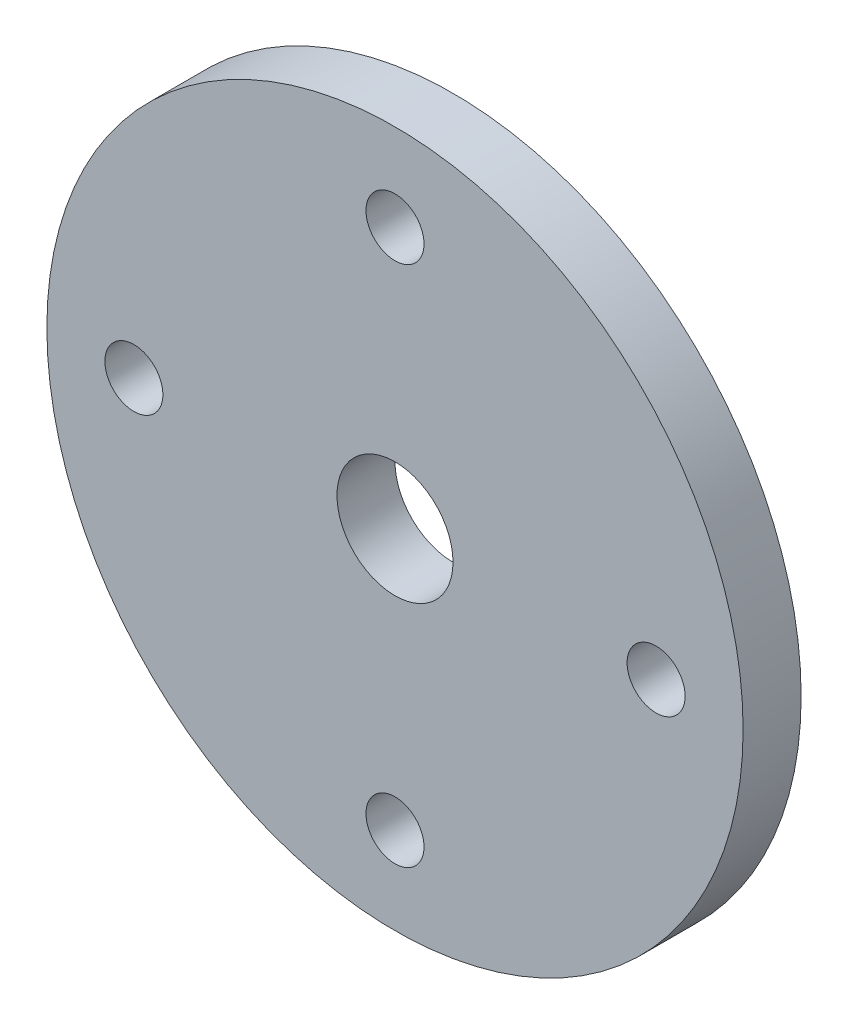
SolidWorks part; units mm, degrees
ref_plane "前视基准面" through (0, 0, 0) normal (0, 0, 1) x (1, 0, 0)
ref_plane "上视基准面" through (0, 0, 0) normal (0, 1, 0) x (1, 0, 0)
ref_plane "右视基准面" through (0, 0, 0) normal (1, 0, 0) x (0, 0, -1)
sketch "草图1" plane through (0, 0, 0) normal (0, 0, 1) x (1, 0, 0)
  circle A0 centre (0, 0) radius 30
  dimension "D1" = 60
extrude "凸台-拉伸1" add sketch "草图1" along normal blind 5
sketch "草图2" plane through (0, 0, 5) normal (0, 0, 1) x (1, 0, 0)
  circle A0 centre (0, 0) radius 5
  dimension "D1" = 10
extrude "切除-拉伸1" cut sketch "草图2" against normal blind 93
sketch "草图3" plane through (0, 0, 5) normal (0, 0, 1) x (1, 0, 0)
  line L0 (0, 22.5) -> (0, -22.5) construction
  line L1 (-22.5, 0) -> (22.5, 0) construction
  circle A0 centre (0, 0) radius 22.5 construction
  point P3 (0, 22.5)
  point P4 (0, -22.5)
  point P5 (-22.5, 0)
  point P6 (22.5, 0)
  dimension "D1" = 45
hole_wizard "M6 螺纹孔1" positions "草图3" profile "草图4" tap size "M6" standard "GB"
sketch "草图4" plane through (22.5, 0, 5) normal (1, 0, 0) x (0, -1, 0)
  line L0 (0, 0) -> (0, 16.5022)
  line L1 (0, 16.5022) -> (2.5, 15)
  line L2 (2.5, 15) -> (2.5, 0)
  line L5 (2.5, 0) -> (0, 0)
  line L10 (0, 16.5022) -> (-2.5, 15) construction
  line L11 (0, -6.35) -> (0, 107.95) construction
  dimension "螺纹孔钻头直径" = 5
  dimension "螺纹孔钻头深度" = 15
  dimension "导头角度" = 118
cosmetic thread "孔螺纹线1" parameters "D1"=12, "D2"=6
cosmetic thread "孔螺纹线2" parameters "D1"=12, "D2"=6
cosmetic thread "孔螺纹线3" parameters "D1"=12, "D2"=6
cosmetic thread "孔螺纹线4" parameters "D1"=12, "D2"=6
